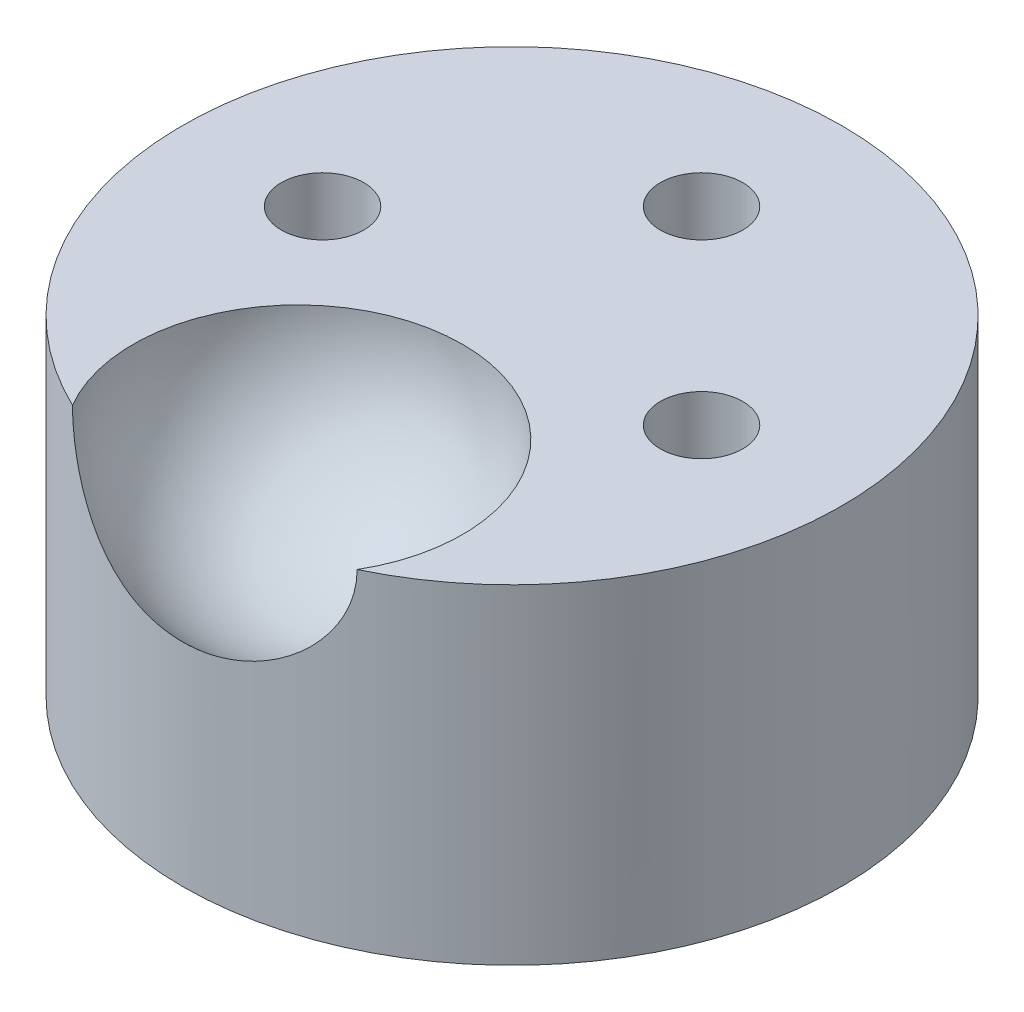
SolidWorks part; units mm, degrees
ref_plane "前视" through (0, 0, 0) normal (0, 0, 1) x (1, 0, 0)
ref_plane "上视" through (0, 0, 0) normal (0, 1, 0) x (1, 0, 0)
ref_plane "右视" through (0, 0, 0) normal (1, 0, 0) x (0, 0, -1)
sketch "草图1" plane through (0, 0, 0) normal (0, 1, 0) x (1, 0, 0)
  circle A0 centre (0, 0) radius 20
extrude "凸台-拉伸1" add sketch "草图1" along normal blind 20
sketch "草图2" plane through (0, 20, 0) normal (0, 1, 0) x (1, 0, 0)
  line L0 (0, -3) -> (0, -23)
  arc A3 (0, -3) -> (0, -23) centre (0, -13) ccw
revolve "切除-旋转1" cut sketch "草图2" angle 360 about L0
sketch "草图4" plane through (0, 0, 0) normal (0, -1, 0) x (1, 0, 0)
  circle A1 centre (0, -11.5) radius 2.5
  circle A5 centre (11.5, 0) radius 2.5
  circle A8 centre (-11.5, 0) radius 2.5
extrude "切除-拉伸1" cut sketch "草图4" against normal through all
chamfer "倒角1" distance 2 angle 30 3 edges at (-11.5, 0, -2.5) (0, 0, -14) (11.5, 0, -2.5)
